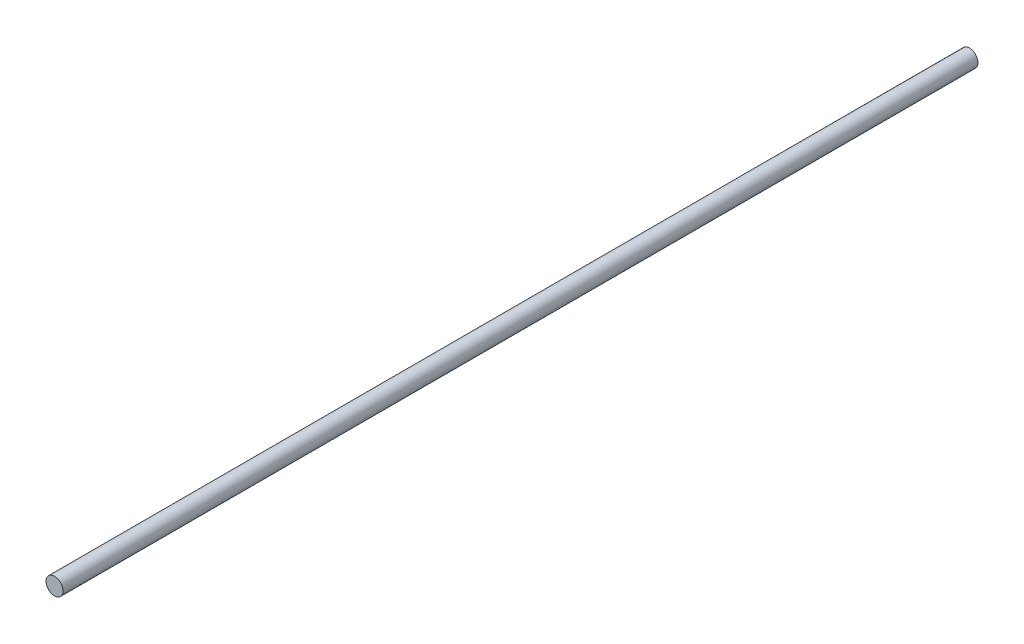
SolidWorks part; units mm, degrees
ref_plane "Plano frontal" through (0, 0, 0) normal (0, 0, 1) x (1, 0, 0)
ref_plane "Plano superior" through (0, 0, 0) normal (0, 1, 0) x (1, 0, 0)
ref_plane "Plano direito" through (0, 0, 0) normal (1, 0, 0) x (0, 0, -1)
sketch "Esboço1" plane through (0, 0, 0) normal (0, 0, 1) x (1, 0, 0)
  circle A0 centre (0, 0) radius 4
  dimension "D1" = 8
extrude "Ressalto-extrusão1" add sketch "Esboço1" along normal blind 430
